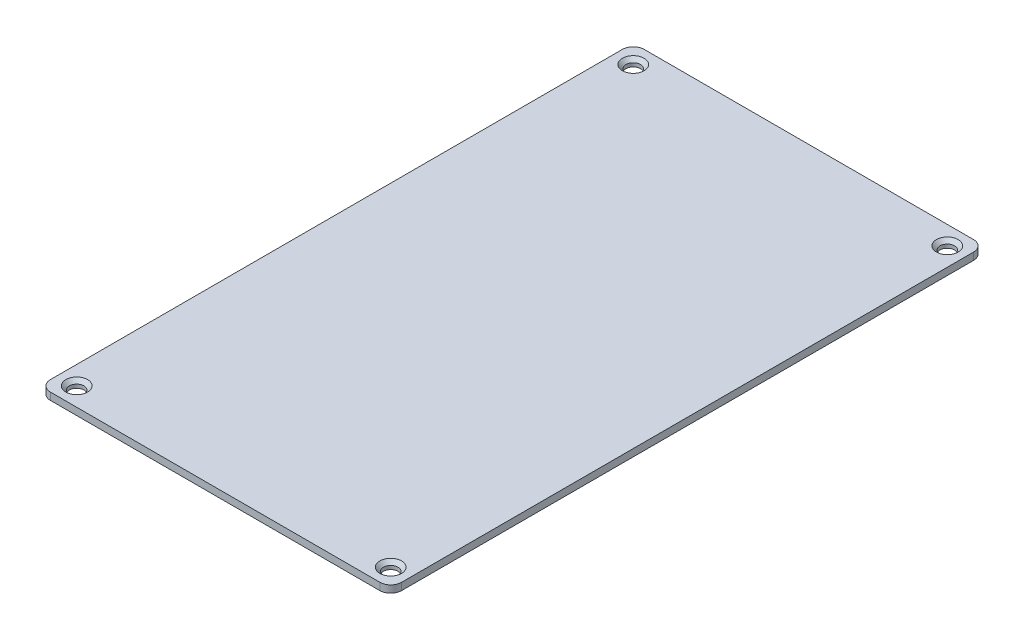
SolidWorks part; units mm, degrees
ref_plane "Front Plane" through (0, 0, 0) normal (0, 0, 1) x (1, 0, 0)
ref_plane "Top Plane" through (0, 0, 0) normal (0, 1, 0) x (1, 0, 0)
ref_plane "Right Plane" through (0, 0, 0) normal (1, 0, 0) x (0, 0, -1)
sketch "Sketch2" plane through (0, 0, 0) normal (0, 1, 0) x (1, 0, 0)
  line L1 (0, 0) -> (93, 0)
  line L2 (0, 0) -> (0, 37.5)
  line L12 (93, 0) -> (93, 160)
  line L17 (95, -2) -> (95, 162)
  line L18 (93, 0) -> (59, 0)
  line L20 (0, 37.5) -> (0, 137.5)
  line L21 (-2, 162) -> (95, 162)
  line L22 (-2, 137.5) -> (-2, 162)
  line L26 (-2, 37.5) -> (-2, 137.5)
  line L28 (0, 137.5) -> (0, 160)
  line L29 (0, 160) -> (93, 160)
  line L34 (-2, -2) -> (-2, 37.5)
  line L43 (-2, -2) -> (95, -2)
  line L44 (46.5, 0) -> (46.5, 160) construction
  line L79 (3.121, 3.121) -> (0, 3.121) construction
  line L80 (3.121, 3.121) -> (3.121, 0) construction
  circle A9 centre (3.121, 3.121) radius 2
  circle A13 centre (89.879, 3.121) radius 2
  circle A14 centre (3.121, 156.879) radius 2
  circle A29 centre (89.879, 156.879) radius 2
  dimension "D3" = 160
  dimension "D1" = 97
extrude "Boss-Extrude1" add sketch "Sketch2" along normal blind 2 contours L34 L43 L17 L21 L22 L26 L28 L29 L12 L1 L2 L20 | L29 L28 L20 L2 L1 L12 A29 A13 A9 A14
fillet "Fillet13" radius 3 4 edges at (95, 1, 2) (-2, 1, 2) (95, 1, -162) (-2, 1, -162)
chamfer "Chamfer1" distance 1 angle 45 4 edges at (89.879, 2, -1.121) (89.879, 2, -154.879) (3.121, 2, -154.879) (3.121, 2, -1.121)
